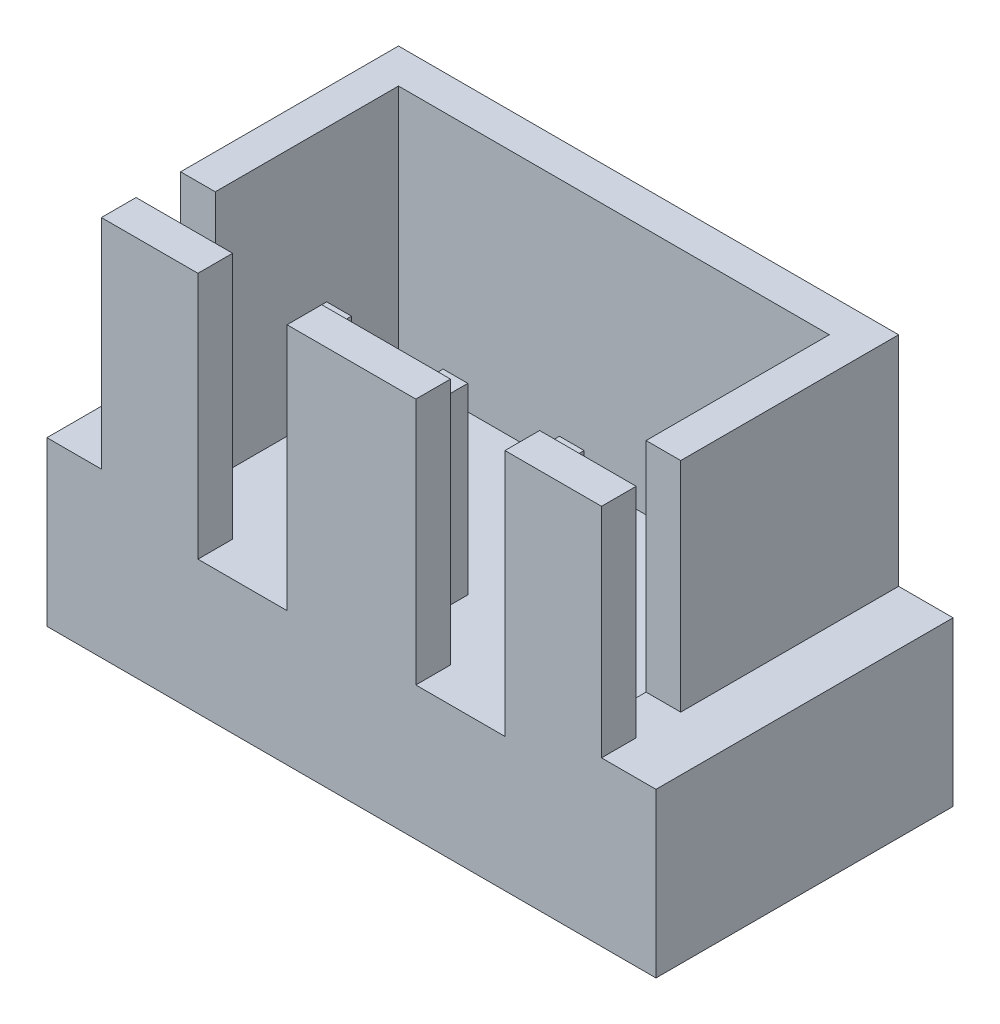
SolidWorks part; units mm, degrees
ref_plane "Front" through (0, 0, 0) normal (0, 0, 1) x (1, 0, 0)
ref_plane "Top" through (0, 0, 0) normal (0, 1, 0) x (1, 0, 0)
ref_plane "Right" through (0, 0, 0) normal (1, 0, 0) x (0, 0, -1)
sketch "Sketch1" plane through (0, 0, 0) normal (0, 1, 0) x (1, 0, 0)
  line L0 (0, 3) -> (0, 0) construction
  line L1 (-6.15, 3) -> (6.15, 3)
  line L2 (-6.15, 3) -> (-6.15, -3)
  line L3 (-6.15, -3) -> (6.15, -3)
  line L4 (6.15, 3) -> (6.15, -3)
  line L5 (0, 0) -> (6.15, 0) construction
  dimension "D1" = 12.3
  dimension "D2" = 6
extrude "Boss-Extrude1" add sketch "Sketch1" along normal blind 7.7
sketch "Sketch2" plane through (0, 7.7, 0) normal (0, 1, 0) x (1, 0, 0)
  line L1 (-4.35, 2.3) -> (4.35, 2.3)
  line L2 (-4.35, 2.3) -> (-4.35, -2.3)
  line L3 (-4.35, -2.3) -> (4.35, -2.3)
  line L4 (4.35, 2.3) -> (4.35, -2.3)
  line L5 (0, 3) -> (0, 0) construction
  line L6 (0, 0) -> (4.118, 0) construction
  line L7 (0, 0) -> (6.15, 0) construction
  dimension "D1" = 8.7
  dimension "D2" = 4.6
extrude "Cut-Extrude1" cut sketch "Sketch2" against normal blind 5
sketch "Sketch3" plane through (0, 7.7, 0) normal (0, 1, 0) x (1, 0, 0)
  line L0 (-6.15, -3) -> (6.15, -3) construction
  line L1 (-6.15, 3) -> (-5.05, 3)
  line L2 (-6.15, 3) -> (-6.15, -3)
  line L3 (-6.15, -3) -> (-5.05, -3)
  line L4 (-5.05, 3) -> (-5.05, -3)
  line L6 (6.15, 3) -> (5.05, 3)
  line L7 (6.15, 3) -> (6.15, -3)
  line L8 (6.15, -3) -> (5.05, -3)
  line L9 (5.05, 3) -> (5.05, -3)
  dimension "D1" = 1.1
extrude "Cut-Extrude2" cut sketch "Sketch3" against normal blind 4.4
sketch "Sketch4" plane through (0, 7.7, 0) normal (0, 1, 0) x (1, 0, 0)
  line L0 (0, 0) -> (0, -3) construction
  line L1 (-6.15, -3) -> (6.15, -3) construction
  line L2 (-4.35, -2.3) -> (4.35, -2.3) construction
  line L3 (-3.1, -2.3) -> (-1.3, -2.3)
  line L4 (-3.1, -2.3) -> (-3.1, -3)
  line L5 (-3.1, -3) -> (-1.3, -3)
  line L6 (-1.3, -2.3) -> (-1.3, -3)
  line L7 (-5.05, -3) -> (-5.05, 3) construction
  line L8 (1.3, -2.3) -> (1.3, -3)
  line L9 (3.1, -3) -> (1.3, -3)
  line L10 (3.1, -2.3) -> (3.1, -3)
  line L11 (3.1, -2.3) -> (1.3, -2.3)
  dimension "D1" = 1.95
  dimension "D2" = 1.8
extrude "Cut-Extrude3" cut sketch "Sketch4" against normal up to surface (5 mm away) up to face at (0, 2.7, 0)
sketch "Sketch5" plane through (0, 7.7, 0) normal (0, 1, 0) x (1, 0, 0)
  line L0 (-5.05, -3) -> (-5.05, 3) construction
  line L1 (-5.05, -1.4) -> (5.05, -1.4)
  line L2 (-5.05, -1.4) -> (-5.05, -2.3)
  line L3 (-5.05, -2.3) -> (5.05, -2.3)
  line L4 (5.05, -1.4) -> (5.05, -2.3)
  line L5 (5.05, 3) -> (5.05, -3) construction
  line L6 (3.1, -2.3) -> (4.35, -2.3) construction
  dimension "D1" = 0.9
extrude "Cut-Extrude4" cut sketch "Sketch5" against normal up to surface (4.4 mm away) up to face at (5.6, 3.3, 0)
sketch "Sketch6" plane through (0, 2.7, 0) normal (0, 1, 0) x (1, 0, 0)
  line L0 (-5.05, -1.4) -> (5.05, -1.4) construction
  line L1 (-0.25, -0.9) -> (0.25, -0.9)
  line L2 (-0.25, -0.9) -> (-0.25, -1.4)
  line L3 (-0.25, -1.4) -> (0.25, -1.4)
  line L4 (0.25, -0.9) -> (0.25, -1.4)
  line L5 (0, 0) -> (0, 4.0905) construction
  line L6 (-2.6, -0.9) -> (-2.1, -0.9)
  line L7 (-2.6, -0.9) -> (-2.6, -1.4)
  line L8 (-2.6, -1.4) -> (-2.1, -1.4)
  line L9 (-2.1, -0.9) -> (-2.1, -1.4)
  line L10 (2.1, -0.9) -> (2.1, -1.4)
  line L11 (2.6, -1.4) -> (2.1, -1.4)
  line L12 (2.6, -0.9) -> (2.6, -1.4)
  line L13 (2.6, -0.9) -> (2.1, -0.9)
  point P14 (0, -0.9)
  dimension "D1" = 1.85
  dimension "D2" = 0.5
extrude "Boss-Extrude2" add sketch "Sketch6" along normal blind 3.7
